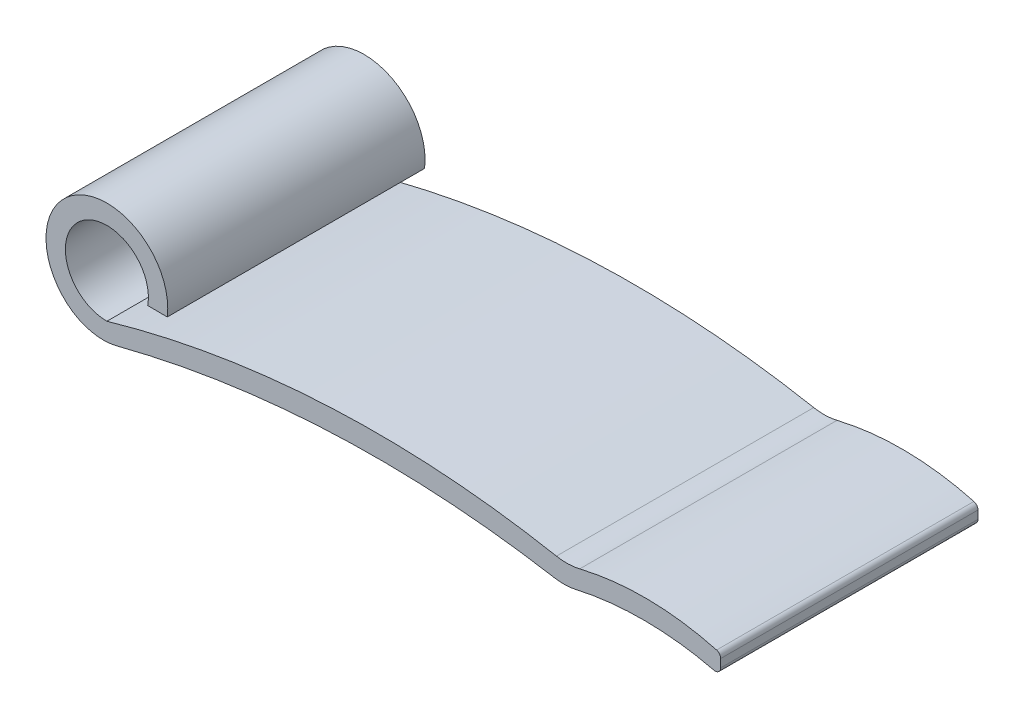
SolidWorks part; units mm, degrees
material "Malleable Cast Iron"
ref_plane "Front Plane" through (0, 0, 0) normal (0, 0, 1) x (1, 0, 0)
ref_plane "Top Plane" through (0, 0, 0) normal (0, 1, 0) x (1, 0, 0)
ref_plane "Right Plane" through (0, 0, 0) normal (1, 0, 0) x (0, 0, -1)
sketch "Sketch1" plane through (0, 0, 0) normal (0, 0, 1) x (1, 0, 0)
  line L0 (28.176, -1.0322) -> (28.176, -1.9212)
  line L3 (1.8741, -0.3419) -> (2.7727, -0.35)
  arc A0 (0, -1.905) -> (1.8741, -0.3419) centre (0, 0) cw
  arc A1 (0, -1.905) -> (21.191, -1.0322) centre (12.3719, -44.5985) cw
  arc A2 (21.191, -1.0322) -> (28.176, -1.0322) centre (24.6835, -13.2425) cw
  arc A3 (28.176, -1.9212) -> (21.0517, -1.9212) centre (24.6139, -15.4657) ccw
  arc A4 (21.0517, -1.9212) -> (-0.0612, -2.794) centre (12.4208, -48.9363) ccw
  arc A5 (-0.0612, -2.794) -> (2.7727, -0.35) centre (0, 0) cw
  dimension "D1" = 1.905
  dimension "D3" = 44.45
  dimension "D5" = 12.7
  dimension "D9" = 2.7947
  dimension "D2" = 21.209
  dimension "D4" = 6.985
  dimension "D6" = 0.889
  dimension "D7" = 0.889
  dimension "D8" = 0.889
extrude "Boss-Extrude1" add sketch "Sketch1" along normal blind 11.811
fillet "Fillet1" radius 2.54 1 edges at (-0.0612, -2.794, 5.9055)
fillet "Fillet2" radius 2.54 1 edges at (21.0517, -1.9212, 5.9055)
fillet "Fillet3" radius 2.54 1 edges at (21.191, -1.0322, 5.9055)
fillet "Fillet4" radius 0.254 2 edges at (28.176, -1.9212, 5.9055) (28.176, -1.0322, 5.9055)
